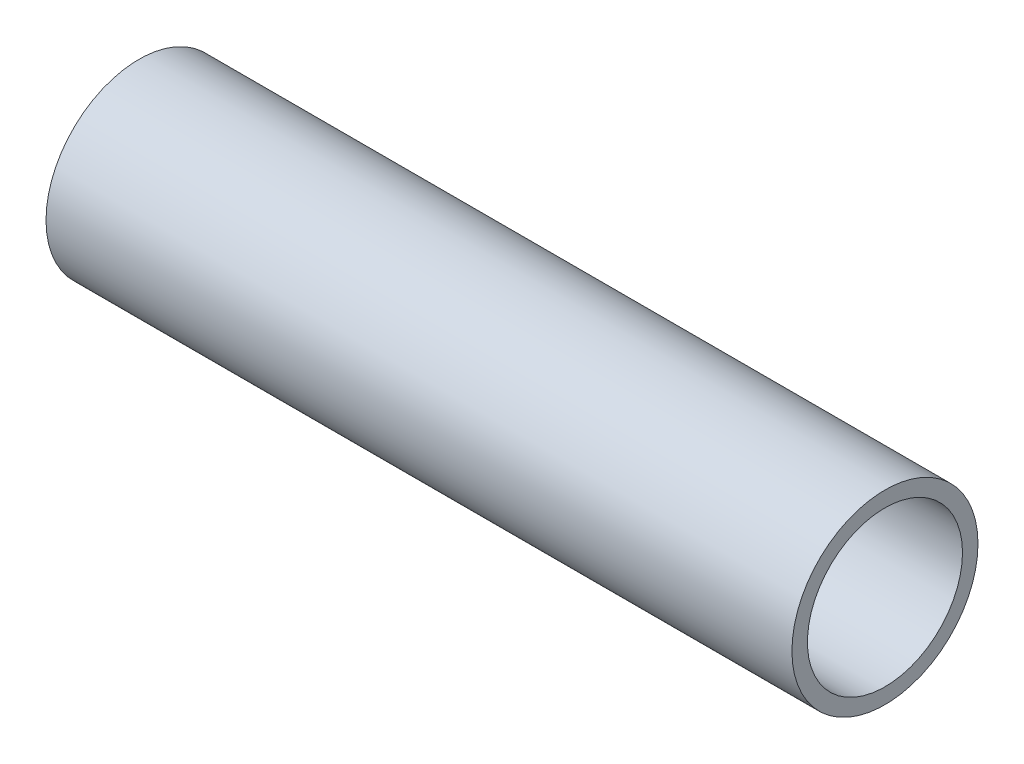
SolidWorks part; units mm, degrees
ref_plane "Front Plane" through (0, 0, 0) normal (0, 0, 1) x (1, 0, 0)
ref_plane "Top Plane" through (0, 0, 0) normal (0, 1, 0) x (1, 0, 0)
ref_plane "Right Plane" through (0, 0, 0) normal (1, 0, 0) x (0, 0, -1)
sketch "Sketch1" plane through (0, 0, 0) normal (1, 0, 0) x (0, 0, -1)
  circle A0 centre (0, 0) radius 10
  circle A1 centre (0, 0) radius 12
  dimension "D1" = 20
  dimension "D2" = 24
extrude "Boss-Extrude1" add sketch "Sketch1" along normal blind 96.21 contours A1 A0
